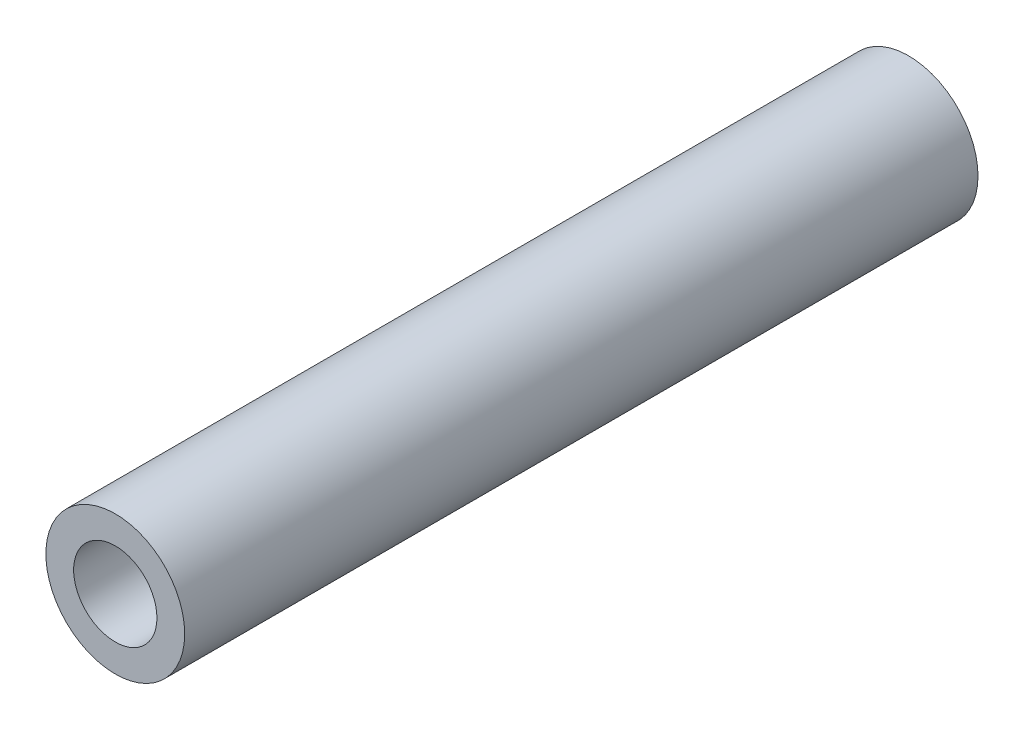
SolidWorks part; units mm, degrees
material "1060 Alloy"
ref_plane "Front Plane" through (0, 0, 0) normal (0, 0, 1) x (1, 0, 0)
ref_plane "Top Plane" through (0, 0, 0) normal (0, 1, 0) x (1, 0, 0)
ref_plane "Right Plane" through (0, 0, 0) normal (1, 0, 0) x (0, 0, -1)
sketch "Sketch1" plane through (0, 0, 0) normal (0, 0, 1) x (1, 0, 0)
  circle A0 centre (-93.8486, 33.5124) radius 2.1 construction
  circle A1 centre (-93.8486, 33.5124) radius 2.1
  circle A2 centre (-93.8486, 33.5124) radius 3.5
  dimension "D1" = 7
extrude "Boss-Extrude1" add sketch "Sketch1" along normal blind 40
